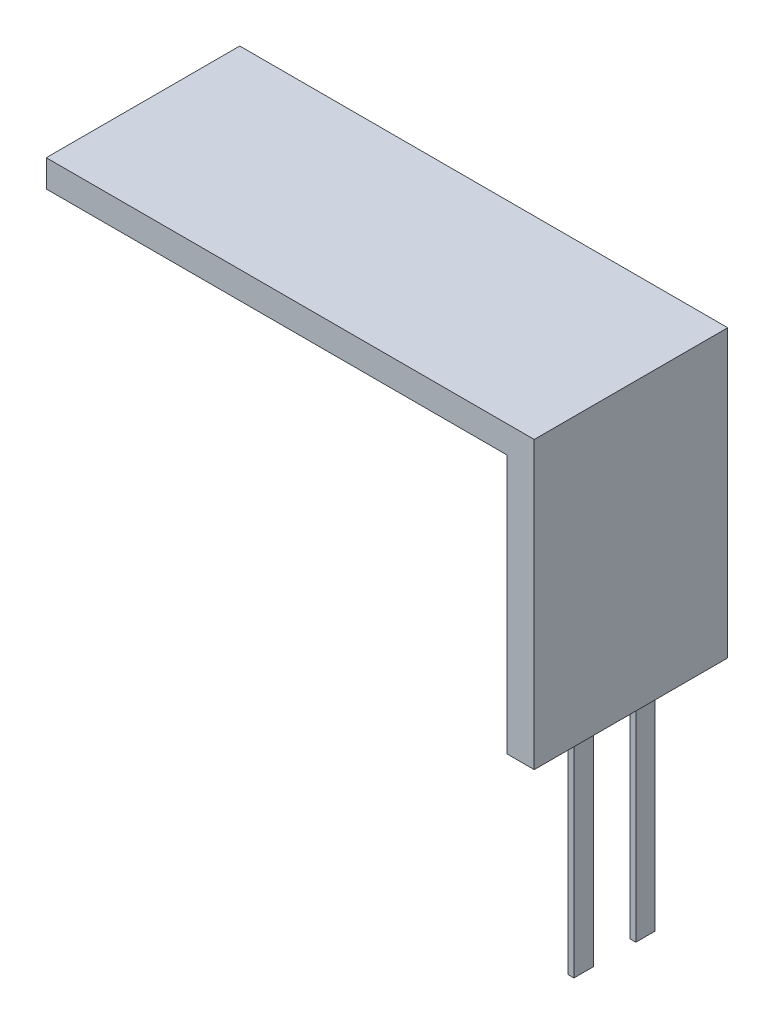
SolidWorks part; units mm, degrees
ref_plane "Front Plane" through (0, 0, 0) normal (0, 0, 1) x (1, 0, 0)
ref_plane "Top Plane" through (0, 0, 0) normal (0, 1, 0) x (1, 0, 0)
ref_plane "Right Plane" through (0, 0, 0) normal (1, 0, 0) x (0, 0, -1)
other "Configuration Table"
sketch "Sketch1" plane through (0, 0, 0) normal (0, 1, 0) x (1, 0, 0)
  line L1 (-0.075, 1.05) -> (0.075, 1.05)
  line L2 (-0.075, 1.05) -> (-0.075, 0.55)
  line L3 (-0.075, 0.55) -> (0.075, 0.55)
  line L4 (0.075, 1.05) -> (0.075, 0.55)
  line L6 (-0.075, -0.55) -> (0.075, -0.55)
  line L7 (-0.075, -0.55) -> (-0.075, -1.05)
  line L8 (-0.075, -1.05) -> (0.075, -1.05)
  line L9 (0.075, -0.55) -> (0.075, -1.05)
extrude "Legs" add sketch "Sketch1" along normal blind 6.1
sketch "Sketch2" plane through (0, 0, 0) normal (0, 1, 0) x (1, 0, 0)
  line L1 (-0.2, 2.5) -> (0.5, 2.5)
  line L2 (-0.2, 2.5) -> (-0.2, -2.5)
  line L3 (-0.2, -2.5) -> (0.5, -2.5)
  line L4 (0.5, 2.5) -> (0.5, -2.5)
extrude "Film up the cell side" add sketch "Sketch2" along normal blind 7.39 from offset 5.6
sketch "Sketch3" plane through (0, 0, 0) normal (0, 1, 0) x (1, 0, 0)
  line L1 (-12.11, 2.5) -> (-0.2, 2.5)
  line L2 (-12.11, 2.5) -> (-12.11, -2.5)
  line L3 (-12.11, -2.5) -> (-0.2, -2.5)
  line L4 (-0.2, 2.5) -> (-0.2, -2.5)
extrude "Film between the cells" add sketch "Sketch3" along normal blind 0.7 from offset 12.29
